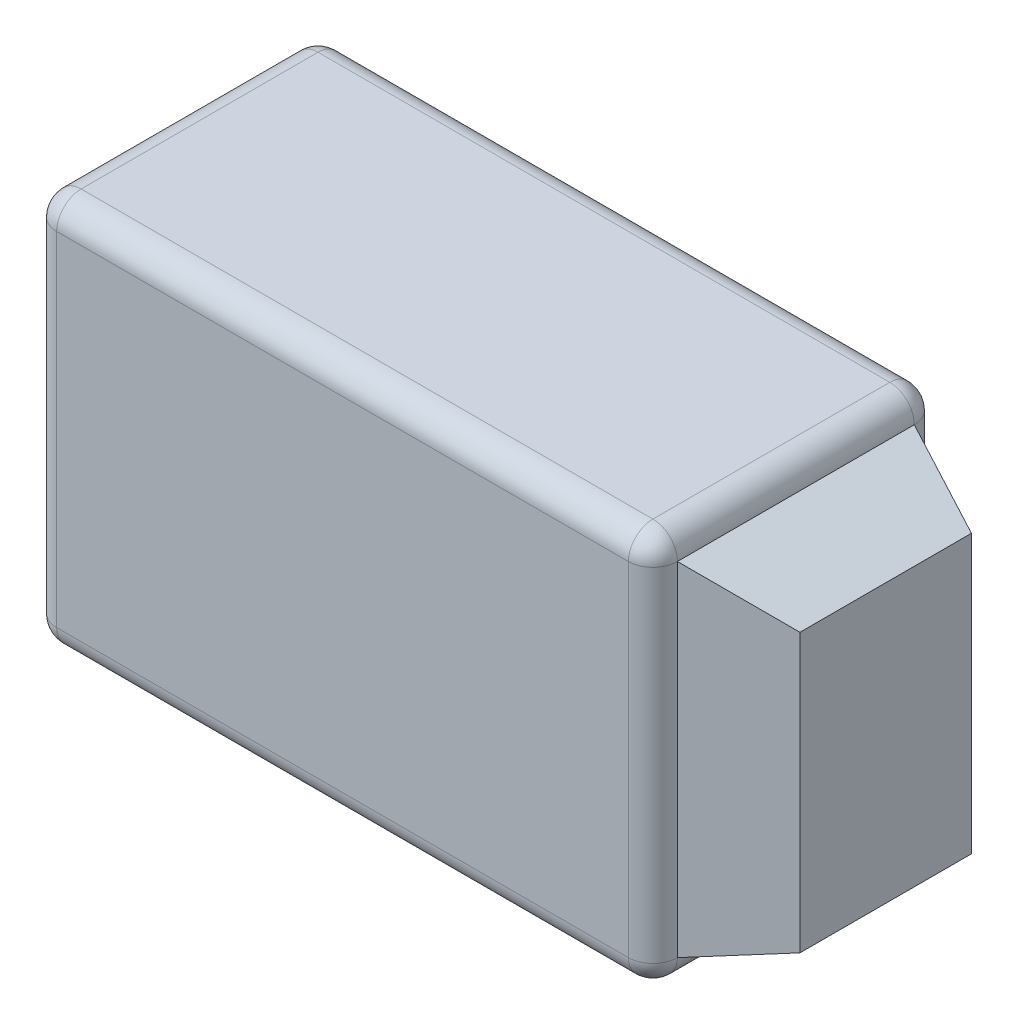
SolidWorks part; units mm, degrees
other "Marcação3"
sketch "Esboço14" plane through (49, 0, 17.5) normal (0.3772, -0.8516, 0.3641) x (-0.5402, -0.5216, -0.6604)
ref_plane "Plano frontal" through (0, 0, 0) normal (0, 0, 1) x (1, 0, 0)
ref_plane "Plano superior" through (0, 0, 0) normal (0, 1, 0) x (1, 0, 0)
ref_plane "Plano direito" through (0, 0, 0) normal (1, 0, 0) x (0, 0, -1)
sketch "Esboço1" plane through (0, 0, 0) normal (0, 1, 0) x (1, 0, 0)
  line L1 (38, -17.5) -> (-38, -17.5)
  line L2 (38, -17.5) -> (38, 17.5)
  line L3 (38, 17.5) -> (-38, 17.5)
  line L4 (-38, -17.5) -> (-38, 17.5)
  line L5 (38, -17.5) -> (-38, 17.5) construction
  line L6 (38, 17.5) -> (-38, -17.5) construction
  point P0 (0, 0)
  dimension "D1" = 76
  dimension "D2" = 35
extrude "Ressalto-extrusão1" add sketch "Esboço1" along normal blind 48
fillet "Filete1" radius 3 12 edges at (38, 24, -17.5) (-38, 24, -17.5) (38, 0, 0) (0, 0, -17.5) (-38, 0, 0) (-38, 24, 17.5) (38, 24, 17.5) (0, 0, 17.5) (0, 48, -17.5) (38, 48, 0) (0, 48, 17.5) (-38, 48, 0)
ref_plane "Plano1" through (38, 45, -14.5) normal (0, 1, 0) x (1, 0, 0)
sketch "Esboço10" plane through (38, 0, 0) normal (1, 0, 0) x (0, 0, -1)
  line L1 (14.5, 45) -> (-14.5, 45)
  line L2 (14.5, 45) -> (14.5, 3)
  line L3 (14.5, 3) -> (-14.5, 3)
  line L4 (-14.5, 45) -> (-14.5, 3)
sketch "Esboço11" plane through (38, 0, 0) normal (1, 0, 0) x (0, 0, -1)
  line L1 (14.5, 45) -> (-14.5, 45)
  line L2 (14.5, 45) -> (14.5, 3)
  line L3 (14.5, 3) -> (-14.5, 3)
  line L4 (-14.5, 45) -> (-14.5, 3)
extrude "Ressalto-extrusão2" add sketch "Esboço11" along normal blind 11 draft 20
